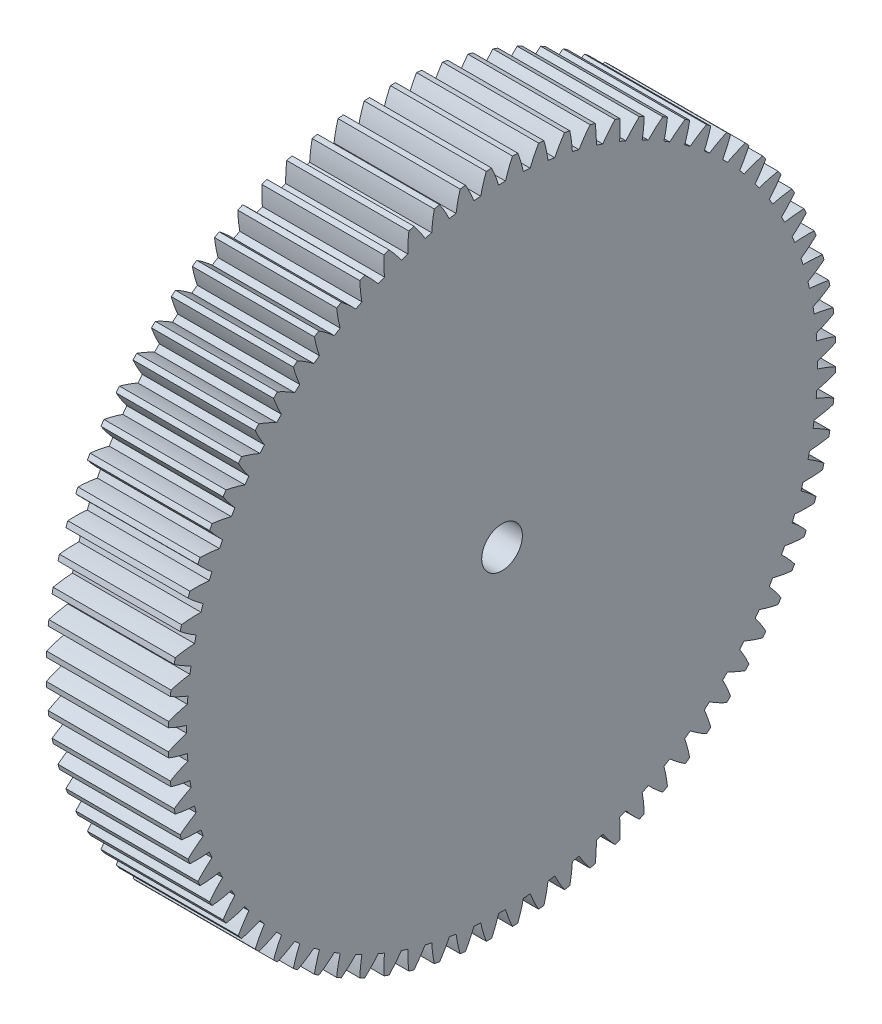
SolidWorks part; units mm, degrees
ref_plane "Plane1" through (0, 0, 0) normal (0, 0, 1) x (1, 0, 0)
ref_plane "Plane2" through (0, 0, 0) normal (0, 1, 0) x (1, 0, 0)
ref_plane "Plane3" through (0, 0, 0) normal (1, 0, 0) x (0, 0, -1)
other "Configuration Table"
sketch "HoldingSke" plane through (0, 0, 0) normal (0, 1, 0) x (1, 0, 0)
  line L0 (0, 0) -> (0.2171, -1.231)
  line L1 (-15, 0) -> (100, 0) construction
  line L2 (0, 0) -> (-2.1039, 2.3779)
  line L3 (0, 0) -> (-11.863, 4.5341)
  line L4 (0, 0) -> (1.4996, 8.5048)
  line L5 (0, 0) -> (-46.8476, -17.4728)
  line L6 (0, 0) -> (-9.9476, -6.7116)
  line L7 (-2.1039, 2.3779) -> (8.6586, 51.2059)
  line L8 (-76.2, 54.61) -> (-75.5, 54.61)
  line L9 (-71.009, 38.7566) -> (-53.1078, 45.2721)
  line L10 (-76.2, 71.12) -> (104.1128, 71.12)
  line L11 (0, 0) -> (-12, 0)
  line L12 (-76.2, 101.6) -> (-76.17, 101.6)
  line L13 (24.9733, 27.94) -> (52.9518, 28.4284)
  line L14 (24.9733, 27.94) -> (24.9743, 27.94)
  line L15 (24.9733, 27.94) -> (100.4006, 29.5858)
  line L16 (-63.627, -0.8) -> (-12.827, -0.8)
  circle A0 centre (0, 0) radius 2
  circle A1 centre (0, 0) radius 30.999
  circle A2 centre (0, 0) radius 37.5
  circle A3 centre (0, 0) radius 2
  dimension "MHD" = 61.998
  dimension "Hub_dia" = 75
  dimension "Bore" = 4
  dimension "MBD" = 4
  dimension "Num_teeth" = 80
  dimension "Pitch" = 1.25
  dimension "Overall_len" = 50
  dimension "Show_teeth" = 80
  dimension "Thickness" = 12
  dimension "OAL" = 50.0001
  dimension "T_dim" = 0.7
  dimension "Ap" = 20
  dimension "H" = 19.05
  dimension "Pitch_radius" = 180.3128
  dimension "Width" = 12
  dimension "Backlash" = 0.03
  dimension "Addendum_fac" = 1
  dimension "Dedendum_fac" = 1.25
  dimension "Clearance_fac" = 0.25
  dimension "Dedendum_add" = 0.001
  dimension "Module" = 0.8
sketch "BasProSke" plane through (0, 0, 0) normal (0, 1, 0) x (1, 0, 0)
  line L0 (-10, 0) -> (60, 0) construction
  line L1 (0, 0) -> (0, 32.8)
  line L2 (0, 0) -> (12, 0)
  line L3 (12, 0) -> (12, 32.8)
  line L4 (12, 32.8) -> (0, 32.8)
  dimension "Thickness" = 12
  dimension "Diameter" = 65.6
revolve "Base-Revolve" add sketch "BasProSke" angle 360 about L0
sketch "TooCutSke" plane through (0, 0, 0) normal (1, 0, 0) x (0, 0, -1)
  line L1 (0, 0) -> (0, 107) construction
  line L2 (0, 0) -> (-0.6808, 31.9928) construction
  line L3 (0, 0) -> (-2.5122, 63.9403) construction
  line L4 (-0.6808, 31.9928) -> (-1.2561, 31.9702) construction
  arc A0 (0.3357, 30.9972) -> (-0.3357, 30.9972) centre (0, 0) ccw
  arc A1 (1.0352, 32.8091) -> (-1.0352, 32.8091) centre (0, 0) ccw
  circle A2 centre (0, 0) radius 32 construction
  circle A3 centre (0, 0) radius 30.0702 construction
  arc A4 (-0.3357, 30.9972) -> (-1.0352, 32.8091) centre (-12.5921, 27.3066) ccw
  arc A5 (1.0352, 32.8091) -> (0.3357, 30.9972) centre (12.5921, 27.3066) ccw
  dimension "Root_dia" = 61.998
  dimension "Overcut_dia" = 65.6508
  dimension "Pitch_dia" = 64
  dimension "Base_dia" = 60.1403
  dimension "Flank_rad" = 12.8
  dimension "Half_ang" = 2.25
  dimension "Half_CT" = 0.5758
extrude "ToothCut" cut sketch "TooCutSke" along normal through all
fillet "Breaks" [suppressed] radius 0.016
fillet "RootFillets" [suppressed] radius 0.201
pattern_circular "TeethCuts" count 80 every 4.5 about axis through (-10, 0, 0) along (1, 0, 0) of "ToothCut", "RootFillets", "Breaks"
sketch "HubNeaOneSke" plane through (0, 0, 0) normal (-1, 0, 0) x (0, 0, 1)
  circle A0 centre (0, 0) radius 30.999
  dimension "Diameter" = 61.998
extrude "HubNearOne" [suppressed] add sketch "HubNeaOneSke" along normal blind 38.0001
sketch "HubNeaBotSke" plane through (0, 0, 0) normal (-1, 0, 0) x (0, 0, 1)
  circle A0 centre (0, 0) radius 30.999
  dimension "Diameter" = 61.998
extrude "HubNearBoth" [suppressed] add sketch "HubNeaBotSke" along normal blind 19
ref_plane "FarPln" through (12, 0, 0) normal (1, 0, 0) x (0, 0, -1)
sketch "HubFarSke" plane through (12, 0, 0) normal (1, 0, 0) x (0, 0, -1)
  circle A0 centre (0, 0) radius 30.999
  dimension "Diameter" = 61.998
extrude "HubFar" [suppressed] add sketch "HubFarSke" along normal blind 19
sketch "BorSke" plane through (0, 0, 0) normal (1, 0, 0) x (0, 0, -1)
  circle A0 centre (0, 0) radius 2
  dimension "Diameter" = 4
extrude "Bore" cut sketch "BorSke" along normal mid plane 100.0001
sketch "KeySke" plane through (0, 0, 0) normal (1, 0, 0) x (0, 0, -1)
  line L0 (-0.8, 0) -> (-0.8, 2.7)
  line L1 (-0.8, 2.7) -> (0.8, 2.7)
  line L2 (0.8, 2.7) -> (0.8, 0)
  line L3 (0, 0) -> (0, 34) construction
  line L4 (-0.8, 0) -> (0.8, 0)
  dimension "Offset" = 2.7
  dimension "Width" = 1.6
extrude "Keyway" [suppressed] cut sketch "KeySke" along normal mid plane 100.0001
pattern_circular "Keyway2" [suppressed] count 2 every 90 about axis through (-10, 0, 0) along (1, 0, 0)
equation "' \"Module@HoldingSke\" = 6.35"
equation "' \"Num_teeth@HoldingSke\" = 12"
equation "' \"Ap@HoldingSke\" =  20"
equation "' \"Ap@HoldingSke\" = 20"
equation "' \"Width@HoldingSke\" = 0.5 * 25.4"
equation "' \"Hub_dia@HoldingSke\"= 1 * 25.4"
equation "' \"Hub_dia@HoldingSke\" = 1 * 25.4"
equation "' \"Overall_len@HoldingSke\" = 1.0 * 25.4"
equation "' \"Bore@HoldingSke\" = 0.75 * 25.4"
equation "' \"T_dim@HoldingSke\" = 0.1 * 25.4"
equation "' \"Width@KeySke\" = 0.25 * 25.4"
equation "' \"Show_teeth@HoldingSke\" = 13"
equation "' \"Backlash@HoldingSke\" = 0.009 * 25.4"
equation "' \"Addendum_fac@HoldingSke\" = 1.0"
equation "' \"Dedendum_fac@HoldingSke\" = 1.25"
equation "' \"Dedendum_add@HoldingSke\" = 0.00005 * 25.4"
equation "' \"Clearance_fac@HoldingSke\" = 0.25"
equation "\"Pitch@HoldingSke\" = 1 / \"Module@HoldingSke\""
equation "\"Overcut_dia@TooCutSke\" = (\"Num_teeth@HoldingSke\" + 2 * \"Addendum_fac@HoldingSke\") / \"Pitch@HoldingSke\" + 0.002 * 25.4"
equation "\"Pitch_dia@TooCutSke\" = \"Num_teeth@HoldingSke\" / \"Pitch@HoldingSke\""
equation "\"Base_dia@TooCutSke\" = \"Num_teeth@HoldingSke\" / \"Pitch@HoldingSke\" * cos((\"Ap@HoldingSke\"  * 3.14159265 / 180))"
equation "\"Root_dia@TooCutSke\" = (\"Num_teeth@HoldingSke\" + 2) / \"Pitch@HoldingSke\" - 2 * (\"Addendum_fac@HoldingSke\" + \"Dedendum_fac@HoldingSke\") / \"Pitch@HoldingSke\" - \"Dedendum_add@HoldingSke\" * 2"
equation "\"Half_ang@TooCutSke\" = 180 / \"Num_teeth@HoldingSke\""
equation "\"Half_CT@TooCutSke\" = \"Num_teeth@HoldingSke\" / \"Pitch@HoldingSke\" * sin((3.14159265 / 2 / \"Num_teeth@HoldingSke\")) / 2 - 7 * \"Backlash@HoldingSke\" / 4"
equation "\"Flank_rad@TooCutSke\" = \"Num_teeth@HoldingSke\" / \"Pitch@HoldingSke\" / 5"
equation "\"Radius@RootFillets\" = \"Clearance_fac@HoldingSke\" / \"Pitch@HoldingSke\" + \"Dedendum_add@HoldingSke\""
equation "\"Break_rad@Breaks\" = 0.02 / \"Pitch@HoldingSke\""
equation "\"Thickness@HoldingSke\" = \"Width@HoldingSke\""
equation "\"OAL@HoldingSke\" = \"Thickness@HoldingSke\""
equation "\"MHD@HoldingSke\" = (\"Num_teeth@HoldingSke\" + 2) / \"Pitch@HoldingSke\" - 2 * (\"Addendum_fac@HoldingSke\" + \"Dedendum_fac@HoldingSke\")  / \"Pitch@HoldingSke\" - \"Dedendum_add@HoldingSke\" * 2"
equation "\"MBD@HoldingSke\" = (\"Num_teeth@HoldingSke\" + 2) / \"Pitch@HoldingSke\" - 2 * (\"Addendum_fac@HoldingSke\" + \"Dedendum_fac@HoldingSke\")  / \"Pitch@HoldingSke\" - \"Dedendum_add@HoldingSke\" * 2 - 0.002 * 25.4"
equation "\"MHD@HoldingSke\" = ((sgn( \"MHD@HoldingSke\" - \"Hub_dia@HoldingSke\" )-1)*( \"MHD@HoldingSke\" - \"Hub_dia@HoldingSke\" ))/-2+ \"Hub_dia@HoldingSke\""
equation "\"MBD@HoldingSke\" = ((sgn( \"MBD@HoldingSke\" - \"Bore@HoldingSke\" )-1)*( \"MBD@HoldingSke\" - \"Bore@HoldingSke\" ))/-2+ \"Bore@HoldingSke\""
equation "\"OAL@HoldingSke\" = ((sgn( \"OAL@HoldingSke\" - \"Overall_len@HoldingSke\" )+1)*( \"OAL@HoldingSke\" - \"Overall_len@HoldingSke\" ))/2 + \"Overall_len@HoldingSke\" + 0.000002 * 25.4"
equation "\"Num_teeth@TeethCuts\" = int( \"Show_teeth@HoldingSke\" ) + 1"
equation "\"Num_teeth@TeethCuts\" = ((sgn( \"Num_teeth@TeethCuts\" - \"Num_teeth@HoldingSke\" )-1)*( \"Num_teeth@TeethCuts\" - \"Num_teeth@HoldingSke\" ))/-2+ \"Num_teeth@HoldingSke\""
equation "\"Num_teeth@TeethCuts\" = ((sgn( \"Num_teeth@TeethCuts\" - 2.0)+1)*( \"Num_teeth@TeethCuts\" - 2.0))/2 +2.0"
equation "\"Angle@TeethCuts\" = 360.0 / \"Num_teeth@HoldingSke\""
equation "\"Diameter@BasProSke\" = (\"Num_teeth@HoldingSke\" + 2 * \"Addendum_fac@HoldingSke\") / \"Pitch@HoldingSke\""
equation "\"Thickness@BasProSke\"  = \"Thickness@HoldingSke\""
equation "' \"Fillet_rad@BasProSke\" =  \"Thickness@HoldingSke\" * 0.05"
equation "' \"Fillet_rad@BasProSke\" = \"Thickness@HoldingSke\" * 0.05"
equation "\"MHD@HoldingSke\" = ((sgn( \"MHD@HoldingSke\" - \"Root_dia@TooCutSke\" )-1)*( \"MHD@HoldingSke\" - \"Root_dia@TooCutSke\" ))/-2+ \"Root_dia@TooCutSke\""
equation "\"Diameter@HubNeaOneSke\" = \"MHD@HoldingSke\""
equation "\"Length@HubNearOne\" = \"OAL@HoldingSke\" - \"Thickness@BasProSke\""
equation "\"Diameter@HubNeaBotSke\" = \"MHD@HoldingSke\""
equation "\"Length@HubNearBoth\" = ( \"OAL@HoldingSke\" - \"Thickness@BasProSke\" ) / 2.0"
equation "\"Thickness@FarPln\" = \"Thickness@BasProSke\""
equation "\"Diameter@HubFarSke\" = \"MHD@HoldingSke\""
equation "\"Length@HubFar\" = ( \"OAL@HoldingSke\" - \"Thickness@BasProSke\" ) / 2.0"
equation "\"Diameter@BorSke\" = \"MBD@HoldingSke\""
equation "\"D1@Bore\" = \"OAL@HoldingSke\" * 2.0"
equation "\"D1@Keyway\" = \"OAL@HoldingSke\" * 2.0"
equation "\"Offset@KeySke\" = \"T_dim@HoldingSke\" + \"MBD@HoldingSke\" / 2.0"
